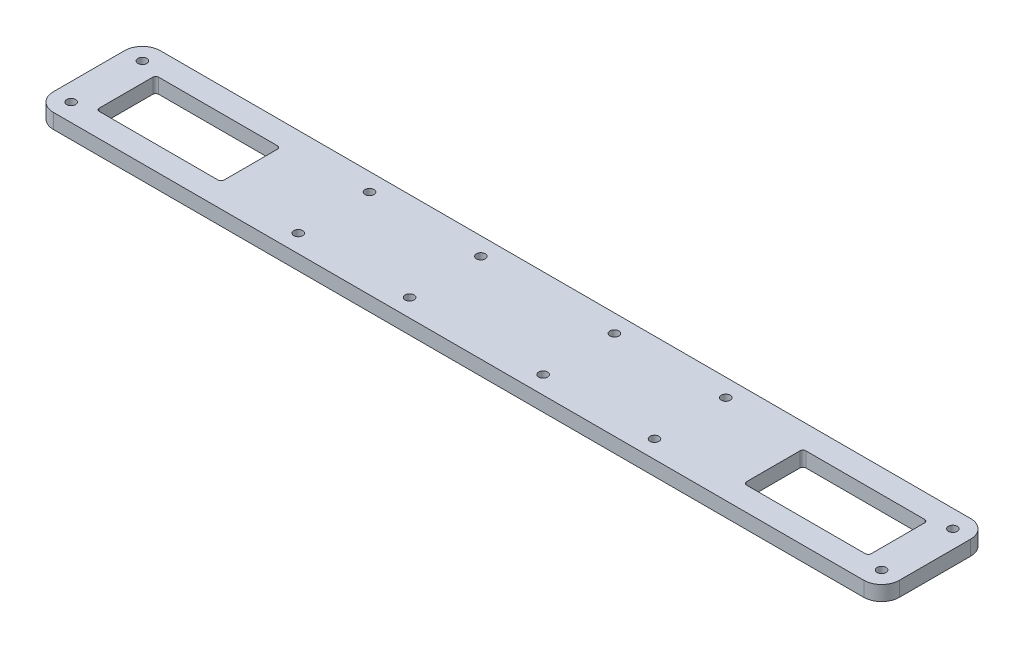
SolidWorks part; units mm, degrees
ref_plane "Front Plane" through (0, 0, 0) normal (0, 0, 1) x (1, 0, 0)
ref_plane "Top Plane" through (0, 0, 0) normal (0, 1, 0) x (1, 0, 0)
ref_plane "Right Plane" through (0, 0, 0) normal (1, 0, 0) x (0, 0, -1)
sketch "Sketch1" plane through (0, 0, 0) normal (0, 1, 0) x (1, 0, 0)
  line L0 (-142.5, 0) -> (142.5, 0) construction
  line L1 (-142.5, -18) -> (142.5, -18)
  line L2 (-142.5, -18) -> (-142.5, 18)
  line L3 (-142.5, 18) -> (142.5, 18)
  line L4 (142.5, -18) -> (142.5, 18)
  line L5 (-142.5, -18) -> (142.5, 18) construction
  line L6 (-142.5, 18) -> (142.5, -18) construction
  line L7 (0, 18) -> (0, -18) construction
  line L8 (-120, -10) -> (-120, 90.0595) construction
  line L9 (-130, 10) -> (-88, 10)
  line L10 (-130, 10) -> (-130, -10)
  line L11 (-130, -10) -> (-88, -10)
  line L12 (-88, 10) -> (-88, -10)
  line L13 (-130, 10) -> (-88, -10) construction
  line L14 (-130, -10) -> (-88, 10) construction
  line L15 (-133, -5) -> (-85, -5) construction
  line L16 (-133, -5) -> (-133, 5) construction
  line L17 (-133, 5) -> (-85, 5) construction
  line L18 (-85, -5) -> (-85, 5) construction
  line L19 (-133, -5) -> (-85, 5) construction
  line L20 (-133, 5) -> (-85, -5) construction
  line L22 (130, 10) -> (88, 10)
  line L23 (130, 10) -> (130, -10)
  line L24 (130, -10) -> (88, -10)
  line L25 (-22.5, -18) -> (-22.5, 18) construction
  line L26 (-28.5, 18) -> (-28.5, -18) construction
  line L27 (-88, 10) -> (-76, 10) construction
  line L28 (-76, 10) -> (-76, -10) construction
  line L29 (-76, -10) -> (-88, -10) construction
  line L30 (88, 10) -> (76, 10) construction
  line L31 (76, 10) -> (76, -10) construction
  line L32 (76, -10) -> (88, -10) construction
  line L33 (88, 10) -> (88, -10)
  circle A0 centre (-85, -5) radius 1.5 construction
  circle A1 centre (-85, 5) radius 1.5 construction
  circle A8 centre (-22.5, -12) radius 1.5
  circle A9 centre (-22.5, 12) radius 1.5
  circle A10 centre (-136.5, -12) radius 1.5
  circle A11 centre (-136.5, 12) radius 1.5
  circle A12 centre (22.5, -12) radius 1.5
  circle A13 centre (22.5, 12) radius 1.5
  circle A14 centre (136.5, -12) radius 1.5
  circle A15 centre (136.5, 12) radius 1.5
  circle A16 centre (-60, 12) radius 1.5
  circle A17 centre (-60, -12) radius 1.5
  circle A20 centre (60, -12) radius 1.5
  circle A21 centre (60, 12) radius 1.5
  point P0 (0, 0)
  point P10 (-109, 0)
  point P15 (-109, 0)
  dimension "D3" = 6
  dimension "D10" = 3
  dimension "D13" = 12
  dimension "D14" = 6
  dimension "D17" = 60
  dimension "D1" = 42
  dimension "D2" = 20
  dimension "D4" = 10
  dimension "D5" = 48
  dimension "D6" = 36
  dimension "D7" = 285
  dimension "D8" = 10
  dimension "D9" = 120
  dimension "D11" = 6
  dimension "D12" = 28.5
  dimension "D15" = 6
  dimension "D16" = 12
extrude "Boss-Extrude2" add sketch "Sketch1" along normal blind 5
fillet "Fillet1" radius 6 4 edges at (142.5, 2.5, 18) (142.5, 2.5, -18) (-142.5, 2.5, 18) (-142.5, 2.5, -18)
fillet "Fillet2" radius 1 8 edges at (88, 2.5, 10) (-130, 2.5, 10) (-88, 2.5, 10) (130, 2.5, 10) (88, 2.5, -10) (130, 2.5, -10) (-88, 2.5, -10) (-130, 2.5, -10)
